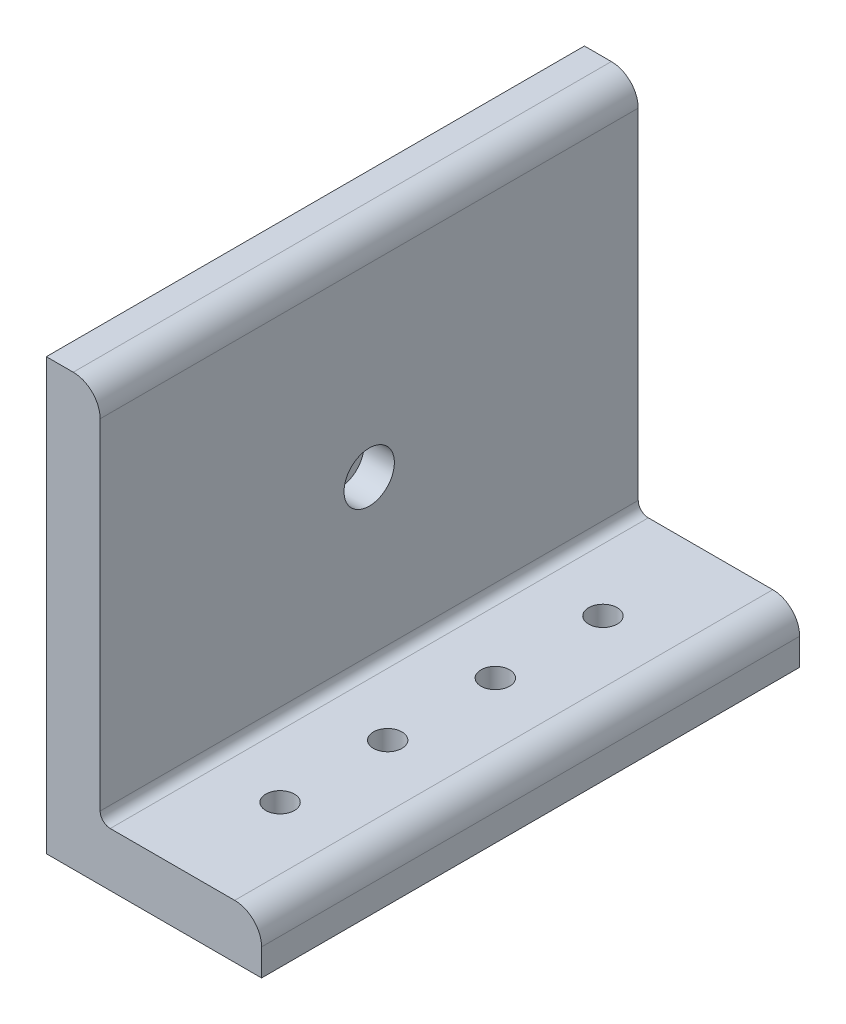
SolidWorks part; units mm, degrees
material "Plain Carbon Steel"
ref_plane "Front Plane" through (0, 0, 0) normal (0, 0, 1) x (1, 0, 0)
ref_plane "Top Plane" through (0, 0, 0) normal (0, 1, 0) x (1, 0, 0)
ref_plane "Right Plane" through (0, 0, 0) normal (1, 0, 0) x (0, 0, -1)
sketch3d "3DSketch1"
  line L0 (-396.6214, -221.175, -32.0639) -> (390.9374, -221.175, -32.0639) construction
  line L1 (390.9374, -221.175, -159.0639) -> (390.9374, -221.175, 94.9361)
  line L2 (517.7786, -227.525, 272.7361) -> (517.7786, -227.525, -336.8639) construction
  line L3 (-396.6214, -221.175, -32.0639) -> (-396.6214, -221.175, -336.8639) construction
  line L5 (-396.6214, -221.175, -32.0639) -> (-396.6214, -221.175, 272.7361) construction
  line L10 (-396.6214, -221.175, -336.8639) -> (-396.6214, -221.175, 272.7361) construction
  line L11 (-396.6214, -221.175, 272.7361) -> (517.7786, -221.175, 272.7361) construction
  point P5 (390.9374, -221.175, -32.0639)
  dimension "D1" = 127
  dimension "D2" = 254
other "L angle L8X4X1(1)"
ref_plane "Plane1" through (390.9374, -221.175, -159.0639) normal (0, 0, 1) x (1, 0, 0)
sketch "Sketch114" plane through (390.9374, -221.175, -159.0639) normal (0, 0, 1) x (1, 0, 0)
  line L0 (0, 0) -> (0, 203.2)
  line L1 (0, 203.2) -> (12.7051, 203.2)
  line L2 (25.4, 190.5051) -> (25.4, 30.1625)
  line L3 (30.1625, 25.4) -> (88.9051, 25.4)
  line L4 (101.6, 12.7051) -> (101.6, 0)
  line L5 (101.6, 0) -> (0, 0)
  arc A0 (101.6, 12.7051) -> (88.9051, 25.4) centre (88.9051, 12.7051) ccw
  arc A1 (12.7051, 203.2) -> (25.4, 190.5051) centre (12.7051, 190.5051) cw
  arc A2 (30.1625, 25.4) -> (25.4, 30.1625) centre (30.1625, 30.1625) cw
  circle A3 centre (0, 0) radius 12.7 construction
  point P10 (0, 101.6)
  point P14 (50.8, 0)
  point P15 (0, 0)
  dimension "D2" = 12.7051
  dimension "Radius_1" = 4.7625
  dimension "Radius_2" = 12.7
  dimension "D1" = 25.4
  dimension "V_leg" = 203.2
  dimension "H_leg" = 101.6
  dimension "Thickness" = 25.4
  dimension "Flat_wid" = 12.7051
sketch "Sketch115" plane through (0, -195.775, 0) normal (0, 1, 0) x (1, 0, 0)
  line L0 (421.0999, 159.0639) -> (479.8425, 159.0639) construction
  line L1 (450.4712, 159.0639) -> (450.4712, -94.9361) construction
  line L2 (479.8425, -94.9361) -> (421.0999, -94.9361) construction
  line L3 (450.4712, 159.0639) -> (450.4712, 108.2639)
  line L4 (450.4712, 108.2639) -> (450.4712, 57.4639)
  line L5 (450.4712, 57.4639) -> (450.4712, 6.6639)
  line L6 (450.4712, 6.6639) -> (450.4712, -44.1361)
  line L7 (450.4712, -44.1361) -> (450.4712, -94.9361)
  point P8 (450.4712, 108.2639)
  point P9 (450.4712, 57.4639)
  point P10 (450.4712, 6.6639)
  point P11 (450.4712, -44.1361)
hole_wizard "1/2 Clearance Hole1" positions "Sketch115" profile "Sketch116" hole size "1/2" standard "ANSI Inch" end condition up to next
sketch "Sketch116" plane through (450.4712, -195.775, 44.1361) normal (1, 0, 0) x (0, 0, 1)
  line L0 (0, 0) -> (0, 25.4)
  line L1 (0, 25.4) -> (6.7462, 25.4)
  line L2 (6.7462, 25.4) -> (6.7462, 0)
  line L5 (6.7462, 0) -> (0, 0)
  line L11 (0, -6.35) -> (0, 107.95) construction
  dimension "Thru Hole Dia." = 13.4925
  dimension "Thru Hole Depth" = 25.4
sketch "Sketch117" plane through (416.3374, 0, 0) normal (1, 0, 0) x (0, 0, -1)
  line L0 (32.0639, -30.6699) -> (32.0639, -118.0002) construction
  line L1 (-94.9361, -30.6699) -> (159.0639, -30.6699) construction
  line L2 (-94.9361, -221.175) -> (159.0639, -221.175) construction
  point P0 (32.0639, -118.0002)
  dimension "D1" = 103.1748
hole_wizard "CBORE for M12 Hex Head Bolt1" positions "Sketch117" profile "Sketch118" counterbore size "M12" standard "ANSI Metric" end condition through all
sketch "Sketch118" plane through (416.3374, -118.0002, -32.0639) normal (0, 1, 0) x (0, 0, -1)
  line L0 (0, 0) -> (0, 25.4)
  line L1 (0, 25.4) -> (6.75, 25.4)
  line L3 (6.75, 25.4) -> (6.75, 14.3)
  line L4 (6.75, 14.3) -> (11.89, 14.3)
  line L5 (11.89, 14.3) -> (11.89, 0)
  line L7 (11.89, 0) -> (0, 0)
  line L11 (0, -6.35) -> (0, 107.95) construction
  dimension "Thru Hole Dia." = 13.5
  dimension "Thru Hole Depth" = 25.4
  dimension "C'Bore Dia." = 23.78
  dimension "C'Bore Depth" = 14.3
